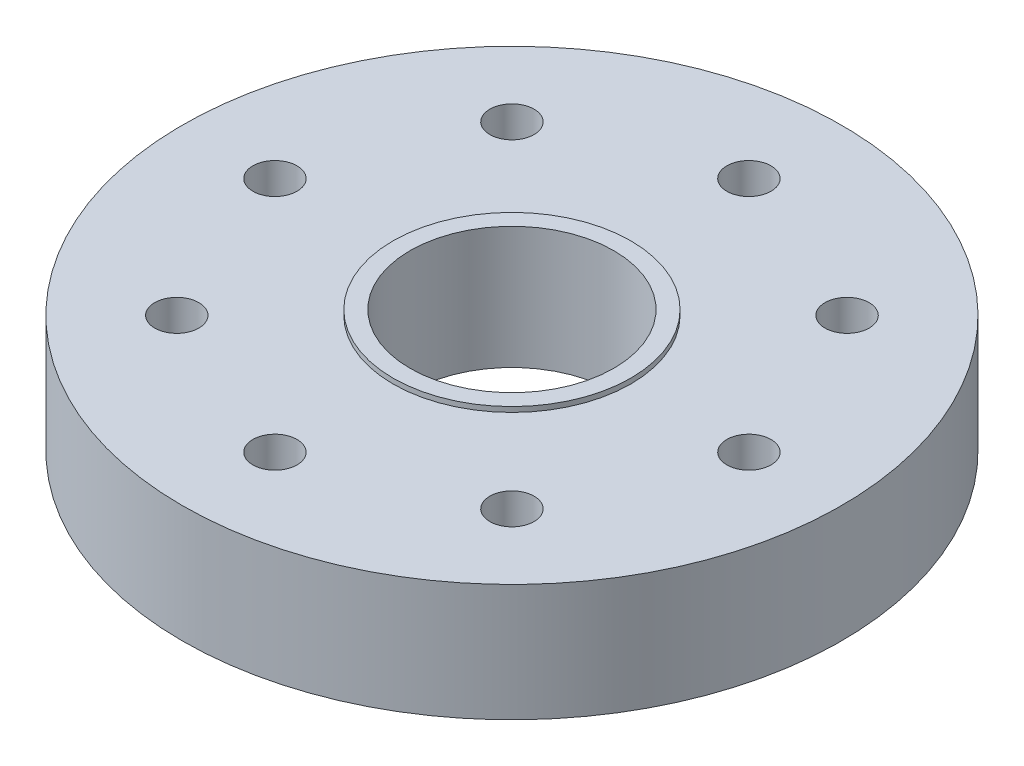
SolidWorks part; units mm, degrees
material "ABS"
ref_plane "Front Plane" through (0, 0, 0) normal (0, 0, 1) x (1, 0, 0)
ref_plane "Top Plane" through (0, 0, 0) normal (0, 1, 0) x (1, 0, 0)
ref_plane "Right Plane" through (0, 0, 0) normal (1, 0, 0) x (0, 0, -1)
sketch "Sketch1" plane through (0, 0, 0) normal (0, 1, 0) x (1, 0, 0)
  circle A0 centre (0, 0) radius 9.7
  dimension "D1" = 19.4
extrude "Boss-Extrude1" add sketch "Sketch1" along normal blind 3.6 contours A0
sketch "Sketch2" plane through (0, 3.6, 0) normal (0, 1, 0) x (1, 0, 0)
  circle A0 centre (-6.975, 0) radius 0.65
  circle A1 centre (-4.9321, 4.9321) radius 0.65
  circle A2 centre (0, 6.975) radius 0.65
  circle A3 centre (4.9321, 4.9321) radius 0.65
  circle A4 centre (6.975, 0) radius 0.65
  circle A5 centre (4.9321, -4.9321) radius 0.65
  circle A6 centre (0, -6.975) radius 0.65
  circle A7 centre (-4.9321, -4.9321) radius 0.65
  point P19 (0, 0)
  dimension "D1" = 1.3
  dimension "D2" = 6.975
  dimension "D3" = 0
  dimension "D4" = 8
extrude "Cut-Extrude1" cut sketch "Sketch2" against normal through all both and the other way through all
sketch "Sketch3" plane through (0, 3.6, 0) normal (0, 1, 0) x (1, 0, 0)
  circle A0 centre (0, 0) radius 3
  dimension "D1" = 6
extrude "Cut-Extrude2" cut sketch "Sketch3" against normal through all both and the other way through all
sketch "Sketch4" plane through (0, 3.6, 0) normal (0, 1, 0) x (1, 0, 0)
  circle A0 centre (0, 0) radius 3
  circle A1 centre (0, 0) radius 3.5
  circle A2 centre (0, 0) radius 9.7
  circle M2 centre (-6.975, 0) radius 0.65
  circle M3 centre (-4.9321, 4.9321) radius 0.65
  circle M4 centre (0, 6.975) radius 0.65
  circle M5 centre (4.9321, 4.9321) radius 0.65
  circle M6 centre (6.975, 0) radius 0.65
  circle M7 centre (4.9321, -4.9321) radius 0.65
  circle M8 centre (0, -6.975) radius 0.65
  circle M9 centre (-4.9321, -4.9321) radius 0.65
  circle M10 centre (0, 0) radius 9.7
  dimension "D1" = 7
extrude "Cut-Extrude3" cut sketch "Sketch4" against normal blind 0.15 contours A1 M10 M2 M4 M6 M8 M9 M7 M5 M3
